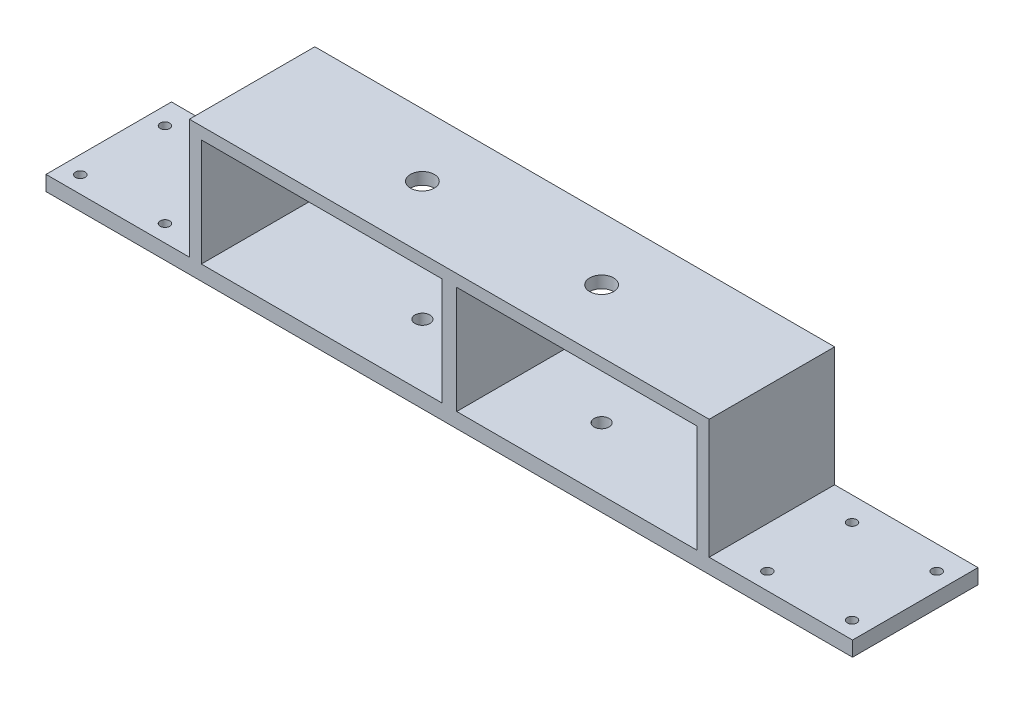
SolidWorks part; units mm, degrees
material "ABS"
ref_plane "Front Plane" through (0, 0, 0) normal (0, 0, 1) x (1, 0, 0)
ref_plane "Top Plane" through (0, 0, 0) normal (0, 1, 0) x (1, 0, 0)
ref_plane "Right Plane" through (0, 0, 0) normal (1, 0, 0) x (0, 0, -1)
sketch "Sketch1" plane through (0, 0, 0) normal (0, 1, 0) x (1, 0, 0)
  line L0 (0, 28.6178) -> (0, -20.5269) construction
  line L1 (85.725, 0) -> (-85.725, 0)
  line L2 (85.725, 0) -> (85.725, 26.67)
  line L3 (85.725, 26.67) -> (-85.725, 26.67)
  line L4 (-85.725, 0) -> (-85.725, 26.67)
  line L5 (-82.025, 21.59) -> (-64.025, 21.59) construction
  line L6 (-73.025, 21.59) -> (-73.025, 0) construction
  line L7 (64.025, 21.59) -> (82.025, 21.59) construction
  line L8 (73.025, 21.59) -> (73.025, 0) construction
  circle A0 centre (64.025, 21.59) radius 1.016
  circle A1 centre (82.025, 21.59) radius 1.016
  circle A2 centre (64.025, 3.59) radius 1.016
  circle A3 centre (82.025, 3.59) radius 1.016
  circle A4 centre (-82.025, 3.59) radius 1.016
  circle A5 centre (-64.025, 3.59) radius 1.016
  circle A6 centre (-82.025, 21.59) radius 1.016
  circle A7 centre (-64.025, 21.59) radius 1.016
  point P0 (0, 0)
  dimension "D5" = 12.7
  dimension "D6" = 18
  dimension "D7" = 2.032
  dimension "D1" = 26.67
  dimension "D2" = 171.45
  dimension "D3" = 5.08
  dimension "D4" = 18
  dimension "D8" = 12.7
extrude "Boss-Extrude1" add sketch "Sketch1" along normal blind 3.175
sketch "Sketch2" plane through (0, 3.175, 0) normal (0, 1, 0) x (1, 0, 0)
  line L0 (-85.725, 13.335) -> (85.725, 13.335) construction
  line L1 (-85.725, 26.67) -> (-85.725, 0) construction
  line L2 (85.725, 0) -> (85.725, 26.67) construction
  line L3 (85.725, 26.67) -> (-85.725, 26.67) construction
  line L4 (-55.245, 0) -> (-52.705, 0)
  line L5 (-55.245, 0) -> (-55.245, 26.67)
  line L6 (-55.245, 26.67) -> (-52.705, 26.67)
  line L7 (-52.705, 0) -> (-52.705, 26.67)
  line L8 (-53.975, 26.67) -> (-53.975, 0) construction
  line L9 (-55.245, 13.335) -> (-52.705, 13.335) construction
  point P6 (-53.975, 13.335)
  point P7 (47.625, 13.335)
  point P8 (-53.975, 13.335)
  dimension "D1" = 171.45
  dimension "D2" = 31.75
  dimension "D3" = 38.1
  dimension "D4" = 26.67
  dimension "D5" = 2.54
extrude "Boss-Extrude2" add sketch "Sketch2" along normal blind 22.86
mirror "Mirror1" about plane through (0, 0, 0) normal (1, 0, 0) of "Boss-Extrude2"
sketch "Sketch3" plane through (-55.245, 0, 0) normal (-1, 0, 0) x (0, 0, 1)
  line L1 (0, 26.035) -> (-26.67, 26.035)
  line L2 (0, 26.035) -> (0, 28.575)
  line L3 (0, 28.575) -> (-26.67, 28.575)
  line L4 (-26.67, 26.035) -> (-26.67, 28.575)
  dimension "D1" = 2.54
  dimension "D2" = 26.67
extrude "Boss-Extrude3" add sketch "Sketch3" against normal up to surface (110.49 mm away) up to face at (55.245, 14.605, -13.335)
sketch "Sketch4" plane through (0, 3.175, 0) normal (0, 1, 0) x (1, 0, 0)
  line L3 (52.705, 26.67) -> (-52.705, 26.67) construction
  line L4 (0, 0) -> (0, 26.67) construction
  line L5 (-52.705, 0) -> (52.705, 0) construction
  line L6 (-19.05, 13.335) -> (19.05, 13.335) construction
  circle A0 centre (-19.05, 13.335) radius 1.5875
  circle A1 centre (19.05, 13.335) radius 1.5875
  point P12 (0, 13.335)
  dimension "D1" = 3.175
  dimension "D2" = 38.1
  dimension "D3" = 3.175
extrude "Cut-Extrude1" cut sketch "Sketch4" against normal up to surface (3.175 mm away) up to face at (0, 0, -13.335)
sketch "Sketch5" plane through (0, 28.575, 0) normal (0, 1, 0) x (1, 0, 0)
  line L0 (0, 26.67) -> (0, 0) construction
  line L1 (55.245, 26.67) -> (-55.245, 26.67) construction
  line L2 (-19.05, 13.335) -> (19.05, 13.335) construction
  circle A0 centre (-19.05, 13.335) radius 2.54
  circle A1 centre (19.05, 13.335) radius 2.54
  point P8 (0, 13.335)
  dimension "D2" = 5.08
  dimension "D3" = 5.08
  dimension "D1" = 38.1
extrude "Cut-Extrude2" cut sketch "Sketch5" against normal up to surface (2.54 mm away) up to face at (0, 26.035, -13.335)
sketch "Sketch6" plane through (0, 3.175, 0) normal (0, 1, 0) x (1, 0, 0)
  line L0 (0, 0) -> (0, 26.67) construction
  line L1 (-52.705, 0) -> (52.705, 0) construction
  line L2 (52.705, 26.67) -> (-52.705, 26.67) construction
  line L4 (-1.5875, 0) -> (1.5875, 0)
  line L5 (-1.5875, 0) -> (-1.5875, 26.67)
  line L6 (-1.5875, 26.67) -> (1.5875, 26.67)
  line L7 (1.5875, 0) -> (1.5875, 26.67)
  line L8 (0, 26.67) -> (0, 0) construction
  line L9 (-1.5875, 13.335) -> (1.5875, 13.335) construction
  point P6 (0, 13.335)
  dimension "D1" = 3.175
extrude "Boss-Extrude4" add sketch "Sketch6" along normal up to surface (22.86 mm away) up to face at (19.05, 26.035, -15.875)
